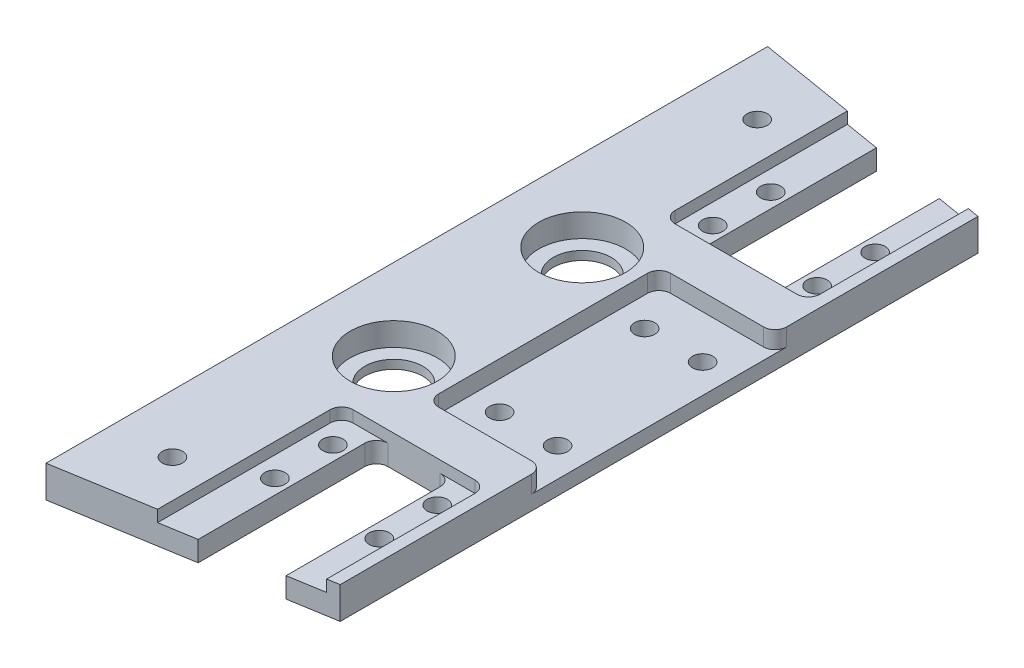
SolidWorks part; units mm, degrees
ref_plane "前视基准面" through (0, 0, 0) normal (0, 0, 1) x (1, 0, 0)
ref_plane "上视基准面" through (0, 0, 0) normal (0, 1, 0) x (1, 0, 0)
ref_plane "右视基准面" through (0, 0, 0) normal (1, 0, 0) x (0, 0, -1)
sketch "草图1" plane through (0, 0, 0) normal (0, 1, 0) x (1, 0, 0)
  line L1 (-17.5, -27.5) -> (17.5, -27.5)
  line L2 (-17.5, -27.5) -> (-17.5, 27.5)
  line L3 (-17.5, 27.5) -> (17.5, 27.5)
  line L4 (17.5, -27.5) -> (17.5, 27.5)
  line L5 (-17.5, -27.5) -> (17.5, 27.5) construction
  line L6 (-17.5, 27.5) -> (17.5, -27.5) construction
  point P0 (0, 0)
  dimension "D1" = 55
  dimension "D2" = 35
extrude "凸台-拉伸1" add sketch "草图1" along normal blind 1
sketch "草图2" plane through (0, 1, 0) normal (0, 1, 0) x (1, 0, 0)
  line L0 (-105.917, 0) -> (-62.25, 0) construction
  line L1 (106.75, 2.25) -> (121.75, 2.25)
  line L2 (-31.4474, 57.1013) -> (151.75, 26.6691)
  line L4 (124.0586, 2.6571) -> (154.0586, 13.5762)
  line L5 (-60.1618, 23.6059) -> (-42.6093, 52.0296)
  line L6 (121.75, 2.25) -> (121.75, 9) construction
  line L7 (121.75, -2.25) -> (121.75, -9) construction
  line L8 (-60.1618, -23.6059) -> (-42.6093, -52.0296)
  line L9 (124.0586, -2.6571) -> (154.0586, -13.5762)
  line L10 (121.75, -9) -> (128.5, -9)
  line L11 (-31.4474, -57.1013) -> (151.75, -26.6691)
  line L12 (106.75, -2.25) -> (121.75, -2.25)
  line L13 (-62.25, 16.25) -> (-62.25, -16.25)
  line L14 (106.75, 2.25) -> (106.75, -2.25)
  line L15 (106.75, 0) -> (124.0666, 0) construction
  arc A0 (-60.1618, 23.6059) -> (-62.25, 16.25) centre (-48.25, 16.25) ccw
  arc A1 (-31.4474, 57.1013) -> (-42.6093, 52.0296) centre (-33.25, 46.25) ccw
  arc A2 (121.75, 2.25) -> (124.0586, 2.6571) centre (121.75, 9) ccw
  arc A3 (154.0586, 13.5762) -> (151.75, 26.6691) centre (151.75, 19.9191) ccw
  arc A4 (154.0586, -13.5762) -> (151.75, -26.6691) centre (151.75, -19.9191) cw
  arc A5 (121.75, -2.25) -> (128.5, -9) centre (121.75, -9) cw
  arc A6 (-31.4474, -57.1013) -> (-42.6093, -52.0296) centre (-33.25, -46.25) cw
  arc A7 (-60.1618, -23.6059) -> (-62.25, -16.25) centre (-48.25, -16.25) cw
  dimension "D2" = 28
  dimension "D3" = 48.25
  dimension "D4" = 22
  dimension "D5" = 15
  dimension "D7" = 13.5
  dimension "D10" = 13.5
  dimension "D11" = 30
  dimension "D1" = 2.25
  dimension "D8" = 20
  dimension "D9" = 30
  dimension "D12" = 15
extrude "凸台-拉伸2" add sketch "草图2" along normal blind 3
sketch "草图3" plane through (0, 4, 0) normal (0, 1, 0) x (1, 0, 0)
  circle A0 centre (-48.25, 16.25) radius 5
  circle A1 centre (-48.25, -16.25) radius 5
  circle A2 centre (-33.25, 46.25) radius 6.6982
  circle A3 centre (151.75, 19.9191) radius 2.5794
  circle A4 centre (121.75, 9) radius 2.5794
  circle A5 centre (121.75, -9) radius 2.5794
  circle A6 centre (151.75, -19.9191) radius 2.5794
  circle A7 centre (-33.25, -46.25) radius 6.6982
  dimension "D1" = 10
extrude "切除-拉伸1" cut sketch "草图3" against normal through all contours A0 | A1
sketch "草图4" plane through (0, 4, 0) normal (0, 1, 0) x (1, 0, 0)
  circle A0 centre (-33.25, 46.25) radius 4
  circle A1 centre (-33.25, -46.25) radius 4
  dimension "D1" = 8
  dimension "D2" = 8
extrude "切除-拉伸2" cut sketch "草图4" against normal blind 2
sketch "草图5" plane through (0, 4, 0) normal (0, 1, 0) x (1, 0, 0)
  circle A0 centre (121.75, 9) radius 2
  circle A1 centre (121.75, -9) radius 2
  circle A2 centre (151.75, 19.9191) radius 2
  circle A3 centre (151.75, -19.9191) radius 2
  dimension "D1" = 4
extrude "切除-拉伸3" cut sketch "草图5" against normal blind 2
sketch "草图8" plane through (0, 1, 0) normal (0, -1, 0) x (1, 0, 0)
  line L1 (-39.75, -26.25) -> (-26.75, -26.25)
  line L2 (-39.75, -26.25) -> (-39.75, -66.25)
  line L3 (-39.75, -66.25) -> (-26.75, -66.25)
  line L4 (-26.75, -26.25) -> (-26.75, -66.25)
  line L5 (-39.75, -26.25) -> (-26.75, -66.25) construction
  line L6 (-39.75, -66.25) -> (-26.75, -26.25) construction
  line L16 (124.0586, 2.6571) -> (154.0586, 13.5762)
  line L17 (151.75, 26.6691) -> (-31.4474, 57.1013)
  line L18 (-42.6093, 52.0296) -> (-60.1618, 23.6059)
  line L19 (-62.25, 16.25) -> (-62.25, -16.25)
  line L20 (-60.1618, -23.6059) -> (-42.6093, -52.0296)
  line L21 (-31.4474, -57.1013) -> (151.75, -26.6691)
  line L22 (154.0586, -13.5762) -> (124.0586, -2.6571)
  line L23 (121.75, -2.25) -> (106.75, -2.25)
  line L24 (106.75, -2.25) -> (106.75, 2.25)
  line L25 (106.75, 2.25) -> (121.75, 2.25)
  line L26 (124.0586, 2.6571) -> (154.0586, 13.5762)
  line L27 (151.75, 26.6691) -> (-31.4474, 57.1013)
  line L28 (-42.6093, 52.0296) -> (-60.1618, 23.6059)
  line L31 (-31.4474, -57.1013) -> (151.75, -26.6691)
  line L32 (154.0586, -13.5762) -> (124.0586, -2.6571)
  line L33 (121.75, -2.25) -> (106.75, -2.25)
  line L34 (106.75, -2.25) -> (106.75, 2.25)
  line L35 (106.75, 2.25) -> (121.75, 2.25)
  arc A8 (154.0586, 13.5762) -> (151.75, 26.6691) centre (151.75, 19.9191) ccw
  arc A9 (-31.4474, 57.1013) -> (-42.6093, 52.0296) centre (-33.25, 46.25) ccw
  arc A10 (-60.1618, 23.6059) -> (-62.25, 16.25) centre (-48.25, 16.25) ccw
  arc A11 (-62.25, -16.25) -> (-60.1618, -23.6059) centre (-48.25, -16.25) ccw
  arc A12 (-42.6093, -52.0296) -> (-31.4474, -57.1013) centre (-33.25, -46.25) ccw
  arc A13 (151.75, -26.6691) -> (154.0586, -13.5762) centre (151.75, -19.9191) ccw
  arc A14 (124.0586, -2.6571) -> (121.75, -2.25) centre (121.75, -9) ccw
  arc A15 (121.75, 2.25) -> (124.0586, 2.6571) centre (121.75, 9) ccw
  arc A16 (154.0586, 13.5762) -> (151.75, 26.6691) centre (151.75, 19.9191) ccw
  arc A17 (-31.4474, 57.1013) -> (-42.6093, 52.0296) centre (-33.25, 46.25) ccw
  arc A18 (-60.1618, 23.6059) -> (-62.25, 16.25) centre (-48.25, 16.25) ccw
  arc A19 (-62.25, -16.25) -> (-60.1618, -23.6059) centre (-48.25, -16.25) ccw
  arc A20 (-42.6093, -52.0296) -> (-31.4474, -57.1013) centre (-33.25, -46.25) ccw
  arc A21 (151.75, -26.6691) -> (154.0586, -13.5762) centre (151.75, -19.9191) ccw
  arc A22 (124.0586, -2.6571) -> (121.75, -2.25) centre (121.75, -9) ccw
  arc A23 (121.75, 2.25) -> (124.0586, 2.6571) centre (121.75, 9) ccw
  point P0 (-33.25, -46.25)
  arc M32 (-42.6093, -52.0296) -> (-31.4474, -57.1013) centre (-33.25, -46.25) ccw
  line M33 (-31.4474, -57.1013) -> (151.75, -26.6691)
  dimension "D1" = 13
  dimension "D2" = 40
  dimension "D3" = 0
extrude "凸台-拉伸3" add sketch "草图8" along normal blind 7 contours L4 L1 L2 M32 M33
mirror "镜向1" about plane through (0, 0, 0) normal (0, 0, 1) of "凸台-拉伸3"
sketch "草图9" plane through (0, -6, 0) normal (0, -1, 0) x (1, 0, 0)
  line L0 (-39.75, -26.25) -> (-26.75, -26.25) construction
  line L2 (-38.25, -53.75) -> (-38.25, -27.75)
  line L3 (-38.25, -27.75) -> (-28.25, -27.75)
  line L4 (-28.25, -53.75) -> (-28.25, -27.75)
  line L5 (-35.5448, -54.7408) -> (-28.25, -27.75) construction
  line L6 (-38.25, -27.75) -> (-31.223, -53.75) construction
  line L8 (-28.25, -53.75) -> (-38.25, -53.75)
  point P0 (-33.25, -46.25)
  dimension "D1" = 10
  dimension "D2" = 1.5
  dimension "D3" = 26
extrude "切除-拉伸4" cut sketch "草图9" against normal through all from offset 1.5 offset against normal yes
mirror "镜向2" about plane through (0, 0, 0) normal (0, 0, 1) of "切除-拉伸4"
sketch "草图10" plane through (0, 0, -53.75) normal (0, 0, 1) x (1, 0, 0)
  line L4 (-38.25, -4.5) -> (-28.25, -4.5)
  line L5 (-28.25, -4.5) -> (-28.25, 4)
  line L6 (-28.25, 4) -> (-38.25, 4)
  line L7 (-38.25, 4) -> (-38.25, -4.5)
  line L8 (-38.25, -4.5) -> (-28.25, -4.5)
  line L9 (-28.25, -4.5) -> (-28.25, 4)
  line L10 (-28.25, 4) -> (-38.25, 4)
  line L11 (-38.25, 4) -> (-38.25, -4.5)
  circle A0 centre (-33.25, -1.5) radius 1.5
  dimension "D2" = 3
  dimension "D3" = 3
  dimension "D1" = 0
extrude "切除-拉伸5" cut sketch "草图10" against normal through all contours A0
mirror "镜向3" about plane through (0, 0, 0) normal (0, 0, 1) of "切除-拉伸5"
sketch "草图11" plane through (0, 4, 0) normal (0, 1, 0) x (1, 0, 0)
  line L0 (-62.25, 16.25) -> (-62.25, 50.4199)
  line L1 (-62.25, -16.25) -> (-62.25, -50.4199)
  line L10 (154.0586, -13.5762) -> (124.0586, -2.6571)
  line L11 (121.75, -2.25) -> (106.75, -2.25)
  line L12 (106.75, -2.25) -> (106.75, 2.25)
  line L13 (106.75, 2.25) -> (121.75, 2.25)
  line L14 (124.0586, 2.6571) -> (154.0586, 13.5762)
  line L15 (151.75, 26.6691) -> (-31.4474, 57.1013)
  line L16 (-42.6093, 52.0296) -> (-60.1618, 23.6059)
  line L17 (-62.25, 16.25) -> (-62.25, -16.25)
  line L18 (-60.1618, -23.6059) -> (-42.6093, -52.0296)
  line L19 (-31.4474, -57.1013) -> (151.75, -26.6691)
  line L20 (154.0586, -13.5762) -> (124.0586, -2.6571)
  line L21 (121.75, -2.25) -> (106.75, -2.25)
  line L22 (106.75, -2.25) -> (106.75, 2.25)
  line L23 (106.75, 2.25) -> (121.75, 2.25)
  line L24 (124.0586, 2.6571) -> (154.0586, 13.5762)
  line L25 (151.75, 26.6691) -> (-50.6113, 60.2847)
  line L26 (-42.6093, 52.0296) -> (-60.1618, 23.6059)
  line L27 (-62.25, 16.25) -> (-62.25, -16.25)
  line L28 (-60.1618, -23.6059) -> (-42.6093, -52.0296)
  line L29 (-50.6113, -60.2847) -> (151.75, -26.6691)
  arc A0 (-62.25, -50.4199) -> (-50.6113, -60.2847) centre (-52.25, -50.4199) ccw
  arc A1 (-50.6113, 60.2847) -> (-62.25, 50.4199) centre (-52.25, 50.4199) ccw
  arc A8 (124.0586, -2.6571) -> (121.75, -2.25) centre (121.75, -9) ccw
  arc A9 (121.75, 2.25) -> (124.0586, 2.6571) centre (121.75, 9) ccw
  arc A10 (154.0586, 13.5762) -> (151.75, 26.6691) centre (151.75, 19.9191) ccw
  arc A11 (-31.4474, 57.1013) -> (-42.6093, 52.0296) centre (-33.25, 46.25) ccw
  arc A12 (-60.1618, 23.6059) -> (-62.25, 16.25) centre (-48.25, 16.25) ccw
  arc A13 (-62.25, -16.25) -> (-60.1618, -23.6059) centre (-48.25, -16.25) ccw
  arc A14 (-42.6093, -52.0296) -> (-31.4474, -57.1013) centre (-33.25, -46.25) ccw
  arc A15 (151.75, -26.6691) -> (154.0586, -13.5762) centre (151.75, -19.9191) ccw
  arc A16 (124.0586, -2.6571) -> (121.75, -2.25) centre (121.75, -9) ccw
  arc A17 (121.75, 2.25) -> (124.0586, 2.6571) centre (121.75, 9) ccw
  arc A18 (154.0586, 13.5762) -> (151.75, 26.6691) centre (151.75, 19.9191) ccw
  arc A19 (-31.4474, 57.1013) -> (-42.6093, 52.0296) centre (-33.25, 46.25) ccw
  arc A20 (-60.1618, 23.6059) -> (-62.25, 16.25) centre (-48.25, 16.25) ccw
  arc A21 (-62.25, -16.25) -> (-60.1618, -23.6059) centre (-48.25, -16.25) ccw
  arc A22 (-42.6093, -52.0296) -> (-31.4474, -57.1013) centre (-33.25, -46.25) ccw
  arc A23 (151.75, -26.6691) -> (154.0586, -13.5762) centre (151.75, -19.9191) ccw
  arc M28 (-31.4474, 57.1013) -> (-42.6093, 52.0296) centre (-33.25, 46.25) ccw
  line M29 (-42.6093, 52.0296) -> (-60.1618, 23.6059)
  arc M30 (-60.1618, 23.6059) -> (-62.25, 16.25) centre (-48.25, 16.25) ccw
  arc M32 (-62.25, -16.25) -> (-60.1618, -23.6059) centre (-48.25, -16.25) ccw
  line M33 (-60.1618, -23.6059) -> (-42.6093, -52.0296)
  arc M34 (-42.6093, -52.0296) -> (-31.4474, -57.1013) centre (-33.25, -46.25) ccw
  dimension "D2" = 10
  dimension "D3" = 10
  dimension "D1" = 0
extrude "凸台-拉伸4" add sketch "草图11" against normal up to surface (3 mm away) contours L25 A1 L0 M30 M29 M28 | L1 A0 L29 M34 M33 M32 up to face at (0, 1, 0)
sketch "草图12" plane through (0, 1, 0) normal (0, -1, 0) x (1, 0, 0)
  circle A0 centre (-48.25, 16.25) radius 9
  circle A1 centre (-48.25, -16.25) radius 9
  circle A2 centre (-48.25, 16.25) radius 5 construction
  circle A3 centre (-48.25, 16.25) radius 5
  circle A4 centre (-48.25, -16.25) radius 5 construction
  circle A5 centre (-48.25, -16.25) radius 5
  dimension "D1" = 18
  dimension "D2" = 18
extrude "凸台-拉伸5" add sketch "草图12" along normal blind 2.5
sketch "草图13" plane through (0, 4, 0) normal (0, 1, 0) x (1, 0, 0)
  circle A0 centre (-48.25, 16.25) radius 7.5
  circle A1 centre (-48.25, -16.25) radius 7.5
  dimension "D1" = 15
  dimension "D2" = 15
extrude "切除-拉伸6" cut sketch "草图13" against normal blind 4
sketch "草图14" plane through (0, 4, 0) normal (0, 1, 0) x (1, 0, 0)
  line L0 (-45.75, 61.25) -> (-45.75, 27.75)
  line L2 (-20.75, 27.75) -> (-20.75, 61.25)
  line L3 (-20.75, 61.25) -> (-45.75, 61.25)
  line L4 (-28.25, 27.75) -> (-28.25, 53.75)
  line L5 (-28.25, 53.75) -> (-38.25, 53.75)
  line L6 (-38.25, 53.75) -> (-38.25, 27.75)
  line L7 (-38.25, 27.75) -> (-28.25, 27.75)
  line L8 (-28.25, 27.75) -> (-28.25, 53.75)
  line L9 (-28.25, 53.75) -> (-38.25, 53.75)
  line L10 (-38.25, 53.75) -> (-38.25, 27.75)
  line L11 (-45.75, 27.75) -> (-20.75, 27.75)
  line L12 (-38.25, 27.75) -> (-28.25, 27.75) construction
  line L13 (-45.75, 61.25) -> (-45.75, 20.25) construction
  line L14 (-20.75, 20.25) -> (-20.75, 61.25) construction
  line L15 (-45.75, 20.25) -> (-20.75, 20.25) construction
  line M19 (151.75, 26.6691) -> (-50.6113, 60.2847)
  line M25 (-28.25, 53.75) -> (-28.25, 27.75)
  line M26 (-28.25, 27.75) -> (-38.25, 27.75)
  line M27 (-38.25, 27.75) -> (-38.25, 53.75)
  line M28 (-38.25, 53.75) -> (-28.25, 53.75)
  dimension "D1" = 0
  dimension "D2" = 7.5
extrude "切除-拉伸7" cut sketch "草图14" against normal blind 2 contours M25 M28 M27 M26 | L0 L11 L2 M27 M28 M25 M19
sketch "草图15" plane through (0, 2, 0) normal (0, 1, 0) x (1, 0, 0)
  line L8 (-28.25, 53.75) -> (-28.25, 27.75)
  line L9 (-28.25, 27.75) -> (-20.75, 27.75)
  line L10 (-20.75, 27.75) -> (-20.75, 55.3243)
  line L11 (-20.75, 55.3243) -> (-45.75, 59.4772)
  line L12 (-45.75, 59.4772) -> (-45.75, 27.75)
  line L13 (-45.75, 27.75) -> (-38.25, 27.75)
  line L14 (-38.25, 27.75) -> (-38.25, 53.75)
  line L15 (-38.25, 53.75) -> (-28.25, 53.75)
  line L19 (-18.75, 54.992) -> (-47.75, 59.8094)
  line L23 (-38.25, 53.75) -> (-28.25, 53.75)
  line L32 (-30.25, 51.75) -> (-30.25, 25.75)
  line L33 (-30.25, 25.75) -> (-18.75, 25.75)
  line L34 (-18.75, 25.75) -> (-18.75, 57.0195)
  line L35 (-18.75, 57.0195) -> (-47.75, 61.8368)
  line L36 (-47.75, 61.8368) -> (-47.75, 25.75)
  line L37 (-47.75, 25.75) -> (-36.25, 25.75)
  line L38 (-36.25, 25.75) -> (-36.25, 51.75)
  line L39 (-36.25, 51.75) -> (-30.25, 51.75)
  line L41 (-30.25, 25.75) -> (-18.75, 25.75)
  line L42 (-18.75, 25.75) -> (-18.75, 54.992)
  line L44 (-47.75, 59.8094) -> (-47.75, 25.75)
  line L45 (-47.75, 25.75) -> (-30.25, 25.75)
  dimension "D1" = 0
  dimension "D2" = 2
extrude "凸台-拉伸6" add sketch "草图15" against normal blind 2 from surface at -1 contours L44 L45 L41 L42 L19 starting at face at (-48.25, 1, 25.25)
sketch "草图16" plane through (0, -6, 0) normal (0, -1, 0) x (1, 0, 0)
  line L0 (-39.75, -55.1241) -> (-39.75, -65.9532)
  line L1 (-39.75, -65.9532) -> (-26.75, -64.7485)
  line L2 (-26.75, -64.7485) -> (-26.75, -56.321)
  line L4 (-26.75, -56.321) -> (-26.75, -26.25)
  line L5 (-26.75, -26.25) -> (-39.75, -26.25)
  line L6 (-39.75, -26.25) -> (-39.75, -55.1241)
  line L7 (-31.4474, -57.1013) -> (-26.75, -56.321)
  line L8 (-26.75, -56.321) -> (-26.75, -26.25)
  line L9 (-26.75, -26.25) -> (-39.75, -26.25)
  line L10 (-39.75, -26.25) -> (-39.75, -55.1241)
  line L11 (-31.4474, -57.1013) -> (-26.75, -56.321)
  arc A1 (-39.75, -55.1241) -> (-31.4474, -57.1013) centre (-33.25, -46.25) ccw
  arc A2 (-39.75, -55.1241) -> (-31.4474, -57.1013) centre (-33.25, -46.25) ccw
  line M6 (-26.75, -56.321) -> (-26.75, -26.25)
  line M7 (-26.75, -26.25) -> (-39.75, -26.25)
  line M8 (-39.75, -26.25) -> (-39.75, -55.1241)
  arc M9 (-39.75, -55.1241) -> (-31.4474, -57.1013) centre (-33.25, -46.25) ccw
  line M10 (-31.4474, -57.1013) -> (-26.75, -56.321)
  dimension "D1" = 0
extrude "切除-拉伸8" cut sketch "草图16" against normal through all contours M10 M6 M7 M8 M9 | L1 L2 L0 M10 M9
mirror "镜向4" about plane through (0, 0, 0) normal (0, 0, 1) of "切除-拉伸7", "切除-拉伸4", "凸台-拉伸6", "切除-拉伸8"
sketch "草图17" plane through (0, 0, 0) normal (0, -1, 0) x (1, 0, 0)
  line L4 (17.5, -27.5) -> (17.5, 27.5)
  line L5 (17.5, 27.5) -> (-17.5, 27.5)
  line L6 (-17.5, 27.5) -> (-17.5, -27.5)
  line L7 (-17.5, -27.5) -> (17.5, -27.5)
  line L8 (17.5, -27.5) -> (17.5, 27.5)
  line L9 (17.5, 27.5) -> (-17.5, 27.5)
  line L10 (-17.5, 27.5) -> (-17.5, -27.5)
  line L11 (-17.5, -27.5) -> (17.5, -27.5)
  dimension "D1" = 0
extrude "切除-拉伸9" cut sketch "草图17" against normal up to surface (1 mm away) up to face at (-48.25, 1, -7.25)
sketch "草图19" plane through (0, 1, 0) normal (0, -1, 0) x (1, 0, 0)
  line L8 (-47.75, -59.8094) -> (-39.75, -58.4805)
  line L9 (-39.75, -58.4805) -> (-39.75, -26.25)
  line L10 (-39.75, -26.25) -> (-26.75, -26.25)
  line L11 (-26.75, -26.25) -> (-26.75, -56.321)
  line L12 (-26.75, -56.321) -> (-18.75, -54.992)
  line L13 (-18.75, -54.992) -> (-18.75, -25.75)
  line L14 (-18.75, -25.75) -> (-47.75, -25.75)
  line L15 (-47.75, -25.75) -> (-47.75, -59.8094)
  line L16 (-18.75, 54.992) -> (-18.75, 25.75)
  line L17 (-18.75, 25.75) -> (-47.75, 25.75)
  line L18 (-47.75, 25.75) -> (-47.75, 59.8094)
  line L19 (-47.75, 59.8094) -> (-50.6113, 60.2847)
  line L20 (-62.25, 50.4199) -> (-62.25, -50.4199)
  line L21 (-50.6113, -60.2847) -> (-47.75, -59.8094)
  line L22 (-47.75, -59.8094) -> (-47.75, -25.75)
  line L23 (-47.75, -25.75) -> (-18.75, -25.75)
  line L24 (-18.75, -25.75) -> (-18.75, -54.992)
  line L25 (-18.75, -54.992) -> (151.75, -26.6691)
  line L26 (154.0586, -13.5762) -> (124.0586, -2.6571)
  line L27 (121.75, -2.25) -> (106.75, -2.25)
  line L28 (106.75, -2.25) -> (106.75, 2.25)
  line L29 (106.75, 2.25) -> (121.75, 2.25)
  line L30 (124.0586, 2.6571) -> (154.0586, 13.5762)
  line L31 (151.75, 26.6691) -> (-18.75, 54.992)
  line L32 (-18.75, 54.992) -> (-18.75, -25.75)
  line L35 (-47.75, 59.8094) -> (-50.6113, 60.2847)
  line L36 (-62.25, 50.4199) -> (-62.25, -50.4199)
  line L37 (-50.6113, -60.2847) -> (-47.75, -59.8094)
  line L40 (-18.75, -25.75) -> (-18.75, -54.992)
  line L48 (-47.75, -59.8094) -> (-39.75, -58.4805)
  line L49 (-39.75, -58.4805) -> (-39.75, -26.25)
  line L50 (-39.75, -26.25) -> (-26.75, -26.25)
  line L51 (-26.75, -26.25) -> (-26.75, -56.321)
  line L52 (-26.75, -56.321) -> (-18.75, -54.992)
  line L53 (-18.75, -54.992) -> (-18.75, -25.75)
  line L56 (-39.75, 26.25) -> (-39.75, 58.4805)
  line L57 (-39.75, 58.4805) -> (-47.75, 59.8094)
  line L58 (-47.75, 59.8094) -> (-47.75, 25.75)
  line L59 (-47.75, 25.75) -> (-18.75, 25.75)
  line L60 (-18.75, 25.75) -> (-18.75, 54.992)
  line L61 (-18.75, 54.992) -> (-26.75, 56.321)
  line L62 (-26.75, 56.321) -> (-26.75, 26.25)
  line L63 (-26.75, 26.25) -> (-39.75, 26.25)
  line L64 (-39.75, 26.25) -> (-39.75, 58.4805)
  line L65 (-39.75, 58.4805) -> (-47.75, 59.8094)
  line L68 (-18.75, 25.75) -> (-18.75, 54.992)
  line L69 (-18.75, 54.992) -> (-26.75, 56.321)
  line L70 (-26.75, 56.321) -> (-26.75, 26.25)
  line L71 (-26.75, 26.25) -> (-39.75, 26.25)
  circle A0 centre (-48.25, 16.25) radius 5 construction
  circle A1 centre (-48.25, 16.25) radius 5
  circle A2 centre (-48.25, -16.25) radius 5 construction
  circle A3 centre (-48.25, -16.25) radius 5
  arc A6 (-50.6113, 60.2847) -> (-62.25, 50.4199) centre (-52.25, 50.4199) ccw
  arc A7 (-62.25, -50.4199) -> (-50.6113, -60.2847) centre (-52.25, -50.4199) ccw
  arc A8 (151.75, -26.6691) -> (154.0586, -13.5762) centre (151.75, -19.9191) ccw
  arc A9 (124.0586, -2.6571) -> (121.75, -2.25) centre (121.75, -9) ccw
  arc A10 (121.75, 2.25) -> (124.0586, 2.6571) centre (121.75, 9) ccw
  arc A11 (154.0586, 13.5762) -> (151.75, 26.6691) centre (151.75, 19.9191) ccw
  arc A12 (-50.6113, 60.2847) -> (-62.25, 50.4199) centre (-52.25, 50.4199) ccw
  arc A13 (-62.25, -50.4199) -> (-50.6113, -60.2847) centre (-52.25, -50.4199) ccw
  circle M23 centre (-48.25, -16.25) radius 9
  circle M24 centre (-48.25, 16.25) radius 9
  line M25 (-18.75, 54.992) -> (-18.75, 25.75)
  line M26 (-18.75, 25.75) -> (-47.75, 25.75)
  line M27 (-47.75, 25.75) -> (-47.75, 59.8094)
  line M28 (-47.75, 59.8094) -> (-50.6113, 60.2847)
  arc M29 (-50.6113, 60.2847) -> (-62.25, 50.4199) centre (-52.25, 50.4199) ccw
  line M30 (-62.25, 50.4199) -> (-62.25, -50.4199)
  arc M31 (-62.25, -50.4199) -> (-50.6113, -60.2847) centre (-52.25, -50.4199) ccw
  line M32 (-50.6113, -60.2847) -> (-47.75, -59.8094)
  line M33 (-47.75, -59.8094) -> (-47.75, -25.75)
  line M34 (-47.75, -25.75) -> (-18.75, -25.75)
  line M35 (-18.75, -25.75) -> (-18.75, -54.992)
  dimension "D1" = 0
  dimension "D2" = 0
  dimension "D3" = 0
extrude "凸台-拉伸8" add sketch "草图19" along direction (0, -1, 0) on the side of the normal up to surface (2.5 mm away) contours L32 M26 M27 M28 M29 M30 M31 M32 M33 M34 M24 M23 | L70 L71 L64 L65 L69 M27 M26 M25 | L51 L52 L48 L49 L50 M35 M34 M33
sketch "草图20" plane through (0, 4, 0) normal (0, 1, 0) x (1, 0, 0)
  line L0 (-39.75, 27.75) -> (-26.75, 27.75)
  line L1 (-26.75, 27.75) -> (-26.75, 26.25)
  line L2 (-26.75, 26.25) -> (-39.75, 26.25)
  line L3 (-39.75, 26.25) -> (-39.75, 27.75) construction
  line L4 (-26.75, 26.25) -> (-39.75, 26.25) construction
  line L5 (-39.75, 26.25) -> (-39.75, 27.75)
  line L6 (-39.75, -26.25) -> (-39.75, -27.75)
  line L7 (-39.75, -27.75) -> (-26.75, -27.75)
  line L8 (-26.75, -27.75) -> (-26.75, -26.25)
  line L9 (-26.75, -26.25) -> (-39.75, -26.25)
  line M7 (-39.75, -26.25) -> (-26.75, -26.25)
  line M8 (-26.75, -26.25) -> (-26.75, -27.75)
  line M24 (-26.75, 27.75) -> (-26.75, 26.25)
  line M25 (-26.75, 26.25) -> (-39.75, 26.25)
  line M26 (-39.75, 26.25) -> (-39.75, 27.75)
  line M36 (-39.75, -27.75) -> (-39.75, -26.25)
extrude "凸台-拉伸9" add sketch "草图20" against normal up to surface (5.5 mm away) contours L0 M26 M25 M24 | L7 M36 M8 M7 up to face at (-48.25, -1.5, 11.25)
sketch "草图21" plane through (0, 4, 0) normal (0, 1, 0) x (1, 0, 0)
  circle A0 centre (121.75, 9) radius 3.5
  circle A1 centre (121.75, -9) radius 3.5
  circle A2 centre (151.75, -19.9191) radius 3.5
  circle A3 centre (151.75, 19.9191) radius 3.5
  dimension "D1" = 7
  dimension "D2" = 7
  dimension "D3" = 7
  dimension "D4" = 7
extrude "切除-拉伸10" cut sketch "草图21" against normal up to surface (2 mm away) up to face at (121.75, 2, -7)
sketch "草图22" plane through (0, 4, 0) normal (0, 1, 0) x (1, 0, 0)
  line L0 (-48.25, 16.25) -> (79.7875, 16.25)
  line L1 (1.75, 16.25) -> (5.75, 16.25) construction
  line L2 (1.75, 18) -> (5.75, 18)
  line L3 (1.75, 14.5) -> (5.75, 14.5)
  line L4 (41.75, 16.25) -> (45.75, 16.25) construction
  line L5 (41.75, 18) -> (45.75, 18)
  line L6 (41.75, 14.5) -> (45.75, 14.5)
  line L7 (81.75, 16.25) -> (85.75, 16.25) construction
  line L8 (81.75, 18) -> (85.75, 18)
  line L9 (81.75, 14.5) -> (85.75, 14.5)
  line L10 (1.75, 31.25) -> (1.75, 35.25) construction
  line L11 (0, 31.25) -> (0, 35.25)
  line L12 (3.5, 31.25) -> (3.5, 35.25)
  line L13 (-3.025, 0) -> (3.025, 0) construction
  line L14 (1.75, -16.25) -> (5.75, -16.25) construction
  line L15 (1.75, -18) -> (5.75, -18)
  line L16 (1.75, -14.5) -> (5.75, -14.5)
  line L17 (41.75, -16.25) -> (45.75, -16.25) construction
  line L18 (41.75, -18) -> (45.75, -18)
  line L19 (41.75, -14.5) -> (45.75, -14.5)
  line L20 (81.75, -16.25) -> (85.75, -16.25) construction
  line L21 (81.75, -18) -> (85.75, -18)
  line L22 (81.75, -14.5) -> (85.75, -14.5)
  line L23 (1.75, -31.25) -> (1.75, -35.25) construction
  line L24 (0, -31.25) -> (0, -35.25)
  line L25 (3.5, -31.25) -> (3.5, -35.25)
  arc A0 (1.75, 18) -> (1.75, 14.5) centre (1.75, 16.25) ccw
  arc A1 (5.75, 14.5) -> (5.75, 18) centre (5.75, 16.25) ccw
  arc A2 (41.75, 18) -> (41.75, 14.5) centre (41.75, 16.25) ccw
  arc A3 (45.75, 14.5) -> (45.75, 18) centre (45.75, 16.25) ccw
  arc A4 (81.75, 18) -> (81.75, 14.5) centre (81.75, 16.25) ccw
  arc A5 (85.75, 14.5) -> (85.75, 18) centre (85.75, 16.25) ccw
  arc A6 (0, 31.25) -> (3.5, 31.25) centre (1.75, 31.25) ccw
  arc A7 (3.5, 35.25) -> (0, 35.25) centre (1.75, 35.25) ccw
  arc A8 (1.75, -18) -> (1.75, -14.5) centre (1.75, -16.25) cw
  arc A9 (5.75, -14.5) -> (5.75, -18) centre (5.75, -16.25) cw
  arc A10 (41.75, -18) -> (41.75, -14.5) centre (41.75, -16.25) cw
  arc A11 (45.75, -14.5) -> (45.75, -18) centre (45.75, -16.25) cw
  arc A12 (81.75, -18) -> (81.75, -14.5) centre (81.75, -16.25) cw
  arc A13 (85.75, -14.5) -> (85.75, -18) centre (85.75, -16.25) cw
  arc A14 (0, -31.25) -> (3.5, -31.25) centre (1.75, -31.25) cw
  arc A15 (3.5, -35.25) -> (0, -35.25) centre (1.75, -35.25) cw
  point P5 (3.75, 16.25)
  point P10 (43.75, 16.25)
  point P17 (83.75, 16.25)
  point P26 (1.75, 33.25)
  point P35 (3.75, -16.25)
  point P42 (43.75, -16.25)
  point P49 (83.75, -16.25)
  point P56 (1.75, -33.25)
  dimension "D1" = 3.5
  dimension "D8" = 40
  dimension "D9" = 40
  dimension "D2" = 4
  dimension "D3" = 4
  dimension "D4" = 4
  dimension "D5" = 3.5
  dimension "D6" = 3.5
  dimension "D7" = 50
  dimension "D10" = 3.5
  dimension "D11" = 4
  dimension "D12" = 15
extrude "切除-拉伸11" cut sketch "草图22" against normal blind 10 contours A9 L16 A8 L15 | A13 L22 A12 L21 | L12 A7 L11 A6 | L3 A1 L0 A0 | L9 A5 L8 A4 | L0 A1 L2 A0 | L25 A15 L24 A14 | L18 A11 L19 A10 | L6 A3 L5 A2
sketch "草图23" plane through (0, 4, 0) normal (0, 1, 0) x (1, 0, 0)
  line L0 (-39.75, 27.75) -> (-45.75, 27.75)
  line L1 (-20.75, 27.75) -> (-45.75, 27.75) construction
  line L2 (-39.75, 27.75) -> (-45.75, 27.75) construction
  line L3 (-26.75, 27.75) -> (-20.75, 27.75)
  line L4 (-20.75, 27.75) -> (-26.75, 27.75) construction
  line L5 (-33.25, 27.75) -> (-33.25, 44.9272) construction
  arc A0 (-50.6113, 60.2847) -> (-62.25, 50.4199) centre (-52.25, 50.4199) ccw construction
  arc A1 (-50.6113, 60.2847) -> (-62.25, 50.4199) centre (-52.25, 50.4199) ccw
  circle A2 centre (-48.25, 16.25) radius 5 construction
  circle A3 centre (-42.25, 32.75) radius 1.75
  circle A4 centre (-24.25, 32.75) radius 1.75
  circle A5 centre (-24.25, 42.75) radius 1.75
  circle A6 centre (-42.25, 42.75) radius 1.75
  dimension "D2" = 3.5
  dimension "D3" = 3.5
  dimension "D4" = 3.5
  dimension "D5" = 3.5
  dimension "D6" = 5
  dimension "D7" = 10
  dimension "D8" = 10
  dimension "D9" = 5
  dimension "D10" = 18
  dimension "D11" = 18
  dimension "D12" = 9
  dimension "D13" = 9
  dimension "D1" = 34.1699
extrude "切除-拉伸12" cut sketch "草图23" against normal blind 10 contours A6 | A3 | A4 | A5
mirror "镜向5" about plane through (0, 0, 0) normal (0, 0, 1) of "切除-拉伸12"
sketch "草图25" plane through (0, 4, 0) normal (0, 1, 0) x (1, 0, 0)
  circle A0 centre (-52.25, -50.4199) radius 1.75
  circle A1 centre (-52.25, 50.4199) radius 1.75
  dimension "D1" = 3.5
  dimension "D2" = 3.5
extrude "切除-拉伸14" cut sketch "草图25" against normal through all
sketch "草图26" plane through (0, 4, 0) normal (0, 1, 0) x (1, 0, 0)
  line L0 (-3.025, 0) -> (3.025, 0) construction
  circle A0 centre (106.75, 25) radius 1
  dimension "D1" = 2
  dimension "D2" = 25
extrude "切除-拉伸15" cut sketch "草图26" against normal blind 10
sketch "草图27" plane through (-18.75, 0, 0) normal (1, 0, 0) x (0, 0, -1)
  line L1 (-83.9984, 24.3466) -> (118.7412, 24.3466)
  line L2 (-83.9984, 24.3466) -> (-83.9984, -35.4638)
  line L3 (-83.9984, -35.4638) -> (118.7412, -35.4638)
  line L4 (118.7412, 24.3466) -> (118.7412, -35.4638)
extrude "切除-拉伸16" cut sketch "草图27" along normal through all
sketch "草图28" plane through (-18.75, 0, 0) normal (1, 0, 0) x (0, 0, -1)
  line L0 (-20, 4) -> (20, 4)
  line L1 (-54.992, 4) -> (54.992, 4) construction
  line L2 (-20, 4) -> (-20, 1)
  line L3 (-20, 1) -> (20, 1)
  line L4 (20, 1) -> (20, 4)
  point P5 (0, 4)
  dimension "D1" = 40
  dimension "D2" = 3
extrude "切除-拉伸17" cut sketch "草图28" against normal blind 20
sketch "草图29" plane through (0, 1, 0) normal (0, 1, 0) x (1, 0, 0)
  line L0 (-18.75, 0) -> (-35.7884, 0)
  line L1 (-18.75, -20) -> (-18.75, 20) construction
  line L3 (-33.75, -12.5) -> (-23.75, -12.5)
  line L4 (-33.75, -12.5) -> (-33.75, 12.5)
  line L5 (-33.75, 12.5) -> (-23.75, 12.5)
  line L6 (-23.75, -12.5) -> (-23.75, 12.5)
  line L7 (-33.75, -12.5) -> (-23.75, 12.5) construction
  line L8 (-33.75, 12.5) -> (-23.75, -12.5) construction
  circle A0 centre (-33.75, 12.5) radius 1.75
  circle A1 centre (-23.75, 12.5) radius 1.75
  circle A2 centre (-23.75, -12.5) radius 1.75
  circle A3 centre (-33.75, -12.5) radius 1.75
  point P6 (-28.75, 0)
  dimension "D1" = 3.5
  dimension "D2" = 10
  dimension "D3" = 10
  dimension "D4" = 25
extrude "切除-拉伸18" cut sketch "草图29" against normal blind 10 contours L6 A1 L5 | L5 A1 L6 | L3 A2 L6 | L6 A2 L3 | L4 A3 L3 | L3 A3 L4 | A0
sketch "草图30" plane through (0, 4, 0) normal (0, 1, 0) x (1, 0, 0)
  line L0 (-62.25, 50.4199) -> (-62.25, 62.2181)
  line L1 (-45.75, 59.4772) -> (-50.6113, 60.2847)
  line L2 (-50.6113, 60.2847) -> (-62.25, 62.2181)
  line L3 (-62.25, -50.4199) -> (-62.25, -62.2181)
  line L4 (-45.75, -59.4772) -> (-50.6113, -60.2847)
  line L5 (-50.6113, -60.2847) -> (-62.25, -62.2181)
  arc A0 (-50.6113, 60.2847) -> (-62.25, 50.4199) centre (-52.25, 50.4199) ccw construction
  arc A1 (-50.6113, 60.2847) -> (-62.25, 50.4199) centre (-52.25, 50.4199) ccw
  arc A2 (-62.25, -50.4199) -> (-50.6113, -60.2847) centre (-52.25, -50.4199) ccw construction
  arc A3 (-62.25, -50.4199) -> (-50.6113, -60.2847) centre (-52.25, -50.4199) ccw
  arc M8 (-50.6113, 60.2847) -> (-62.25, 50.4199) centre (-52.25, 50.4199) ccw
  arc M10 (-62.25, -50.4199) -> (-50.6113, -60.2847) centre (-52.25, -50.4199) ccw
extrude "凸台-拉伸10" add sketch "草图30" against normal up to surface (5.5 mm away) contours L2 L0 M8 | L5 L3 M10 up to face at (-33.75, -1.5, -14.25)
fillet "圆角1" radius 2 10 edges at (-38.75, 2.5, -20) (-38.75, 2.5, 20) (-20.75, 3, -27.75) (-45.75, 3, -27.75) (-45.75, 3, 27.75) (-20.75, 3, 27.75) (-39.75, 0.25, -27.75) (-26.75, 0.25, -27.75) (-26.75, 0.25, 27.75) (-39.75, 0.25, 27.75)
fillet "圆角3" radius 2 2 edges at (-18.75, 2.5, -20) (-18.75, 2.5, 20)
